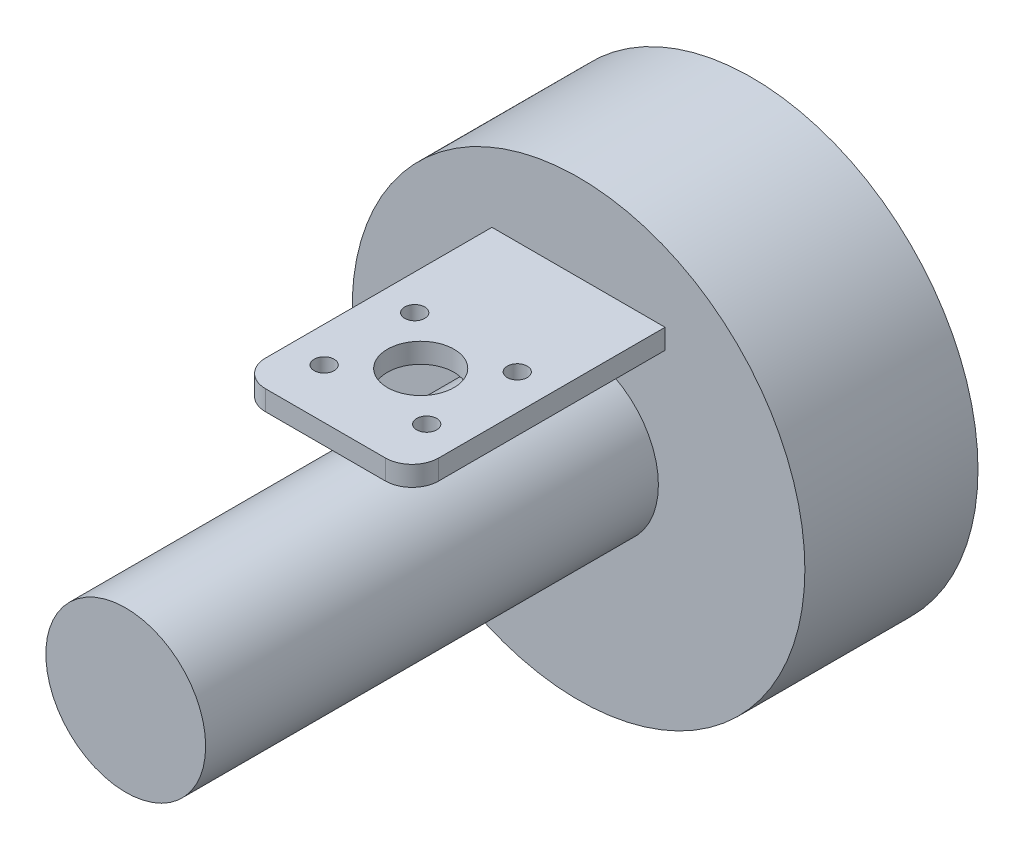
SolidWorks part; units mm, degrees
material "Бутил"
ref_plane "Спереди" through (0, 0, 0) normal (0, 0, 1) x (1, 0, 0)
ref_plane "Сверху" through (0, 0, 0) normal (0, 1, 0) x (1, 0, 0)
ref_plane "Справа" through (0, 0, 0) normal (1, 0, 0) x (0, 0, -1)
sketch "Эскиз1" plane through (0, 0, 0) normal (1, 0, 0) x (0, 0, -1)
  line L1 (0, 0) -> (68, 0)
  line L2 (0, 0) -> (0, 12)
  line L3 (0, 12) -> (68, 12)
  line L4 (68, 0) -> (68, 12)
  line L5 (68, 0) -> (94, 0)
  line L6 (68, 0) -> (68, 34)
  line L7 (68, 34) -> (94, 34)
  line L8 (94, 0) -> (94, 34)
  dimension "D1" = 68
  dimension "D2" = 12
revolve "Повернуть1" add sketch "Эскиз1" angle 360 about L1
sketch "Эскиз2" plane through (0, 0, -68) normal (0, 0, 1) x (1, 0, 0)
  line L0 (0, 0) -> (0, 21) construction
  line L1 (0, 21) -> (13, 21)
  line L2 (0, 21) -> (-13, 21)
  line L3 (13, 21) -> (13, 18)
  line L4 (13, 18) -> (-13, 18)
  line L5 (-13, 18) -> (-13, 21)
  dimension "D1" = 13
  dimension "D2" = 13
  dimension "D3" = 3
  dimension "D4" = 21
extrude "Бобышка-Вытянуть1" add sketch "Эскиз2" along normal blind 38
sketch "Эскиз3" plane through (0, 21, 0) normal (0, 1, 0) x (1, 0, 0)
  line L0 (0, 30) -> (0, 37.5) construction
  line L1 (13, 30) -> (-13, 30) construction
  line L2 (7.7, 37.5) -> (7.7, 51.1)
  line L3 (7.7, 51.1) -> (-7.7, 51.1)
  line L4 (0, 51.1) -> (0, 37.5) construction
  circle A0 centre (7.7, 37.5) radius 1.5
  circle A1 centre (-7.7, 37.5) radius 1.5
  circle A2 centre (7.7, 51.1) radius 1.5
  circle A3 centre (-7.7, 51.1) radius 1.5
  circle A4 centre (0, 44.3) radius 5
  dimension "D2" = 3
  dimension "D3" = 3
  dimension "D9" = 3
  dimension "D10" = 3
  dimension "D11" = 10
  dimension "D1" = 7.5
  dimension "D4" = 7.7
  dimension "D5" = 7.5
  dimension "D6" = 7.7
  dimension "D7" = 13.6
  dimension "D8" = 15.4
extrude "Вырез-Вытянуть1" cut sketch "Эскиз3" against normal up to surface (3 mm away)
fillet "Скругление1" radius 4 2 edges at (-13, 19.5, -30) (13, 19.5, -30)
